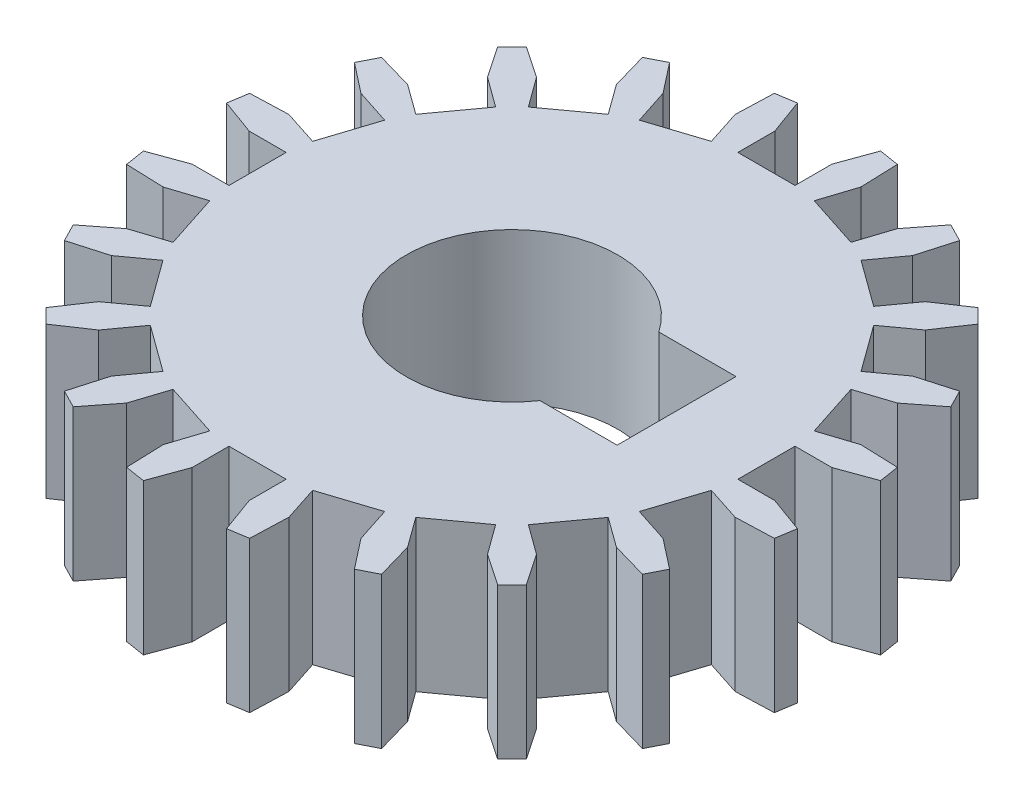
SolidWorks part; units mm, degrees
ref_plane "前视基准面" through (0, 0, 0) normal (0, 0, 1) x (1, 0, 0)
ref_plane "上视基准面" through (0, 0, 0) normal (0, 1, 0) x (1, 0, 0)
ref_plane "右视基准面" through (0, 0, 0) normal (1, 0, 0) x (0, 0, -1)
other "Configuration Table"
sketch "草图1" plane through (0, 0, 0) normal (0, 1, 0) x (1, 0, 0)
  line L0 (0, 0) -> (25.9017, 0) construction
  line L1 (5.7882, 3.9366) -> (10.9003, 3.9366)
  line L3 (5.7882, -3.9366) -> (10.9003, -3.9366)
  line L4 (10.9003, 3.9366) -> (10.9003, -3.9366)
  arc A0 (5.7882, 3.9366) -> (5.7882, -3.9366) centre (0, 0) ccw
  circle A1 centre (0, 0) radius 25
  dimension "D1" = 14
  dimension "D2" = 50
extrude "凸台-拉伸1" add sketch "草图1" along normal blind 10
sketch "草图2" plane through (0, 10, 0) normal (0, 1, 0) x (1, 0, 0)
  line L0 (0, 33.9468) -> (0, 0) construction
  line L1 (-1.893, 16.8504) -> (1.893, 16.8504)
  line L2 (1.893, 16.8504) -> (1.893, 19.2949)
  line L3 (1.893, 19.2949) -> (6.011, 30.609)
  line L4 (6.011, 30.609) -> (-6.011, 30.609)
  line L5 (-6.011, 30.609) -> (-1.893, 19.2949)
  line L6 (-1.893, 19.2949) -> (-1.893, 16.8504)
  line L7 (0, 0) -> (3.952, 24.952) construction
  line L8 (0, 0) -> (-3.952, 24.952) construction
  point P5 (0, 0)
  dimension "D1" = 20
  dimension "D2" = 18
extrude "切除-拉伸1" cut sketch "草图2" against normal through all both
sketch "草图3" plane through (0, 0, 0) normal (0, 0, 1) x (1, 0, 0)
  line L0 (0, 21.216) -> (0, 0) construction
  line L1 (-25, 0) -> (25, 0) construction
pattern_circular "阵列(圆周)1" count 20 over 360 about axis through (0, 0, 0) along (0, 1, 0) of "切除-拉伸1"
sketch "草图4" plane through (0, 0, 0) normal (0, 1, 0) x (1, 0, 0)
  line L0 (-5.0647, 21.2932) -> (-2.3989, 21.7154)
  line L1 (-2.3989, 21.7154) -> (-3.2156, 26.8714)
  line L2 (-3.2156, 26.8714) -> (-6.4217, 26.3636)
  line L3 (-6.4217, 26.3636) -> (-5.0647, 21.2932)
  line L4 (-4.1621, 18.9355) -> (-1.893, 19.2949) construction
extrude "切除-拉伸2" cut sketch "草图4" along normal through all both
pattern_circular "阵列(圆周)2" count 20 over 360 about axis through (0, 0, 0) along (0, 1, 0) of "切除-拉伸2"
